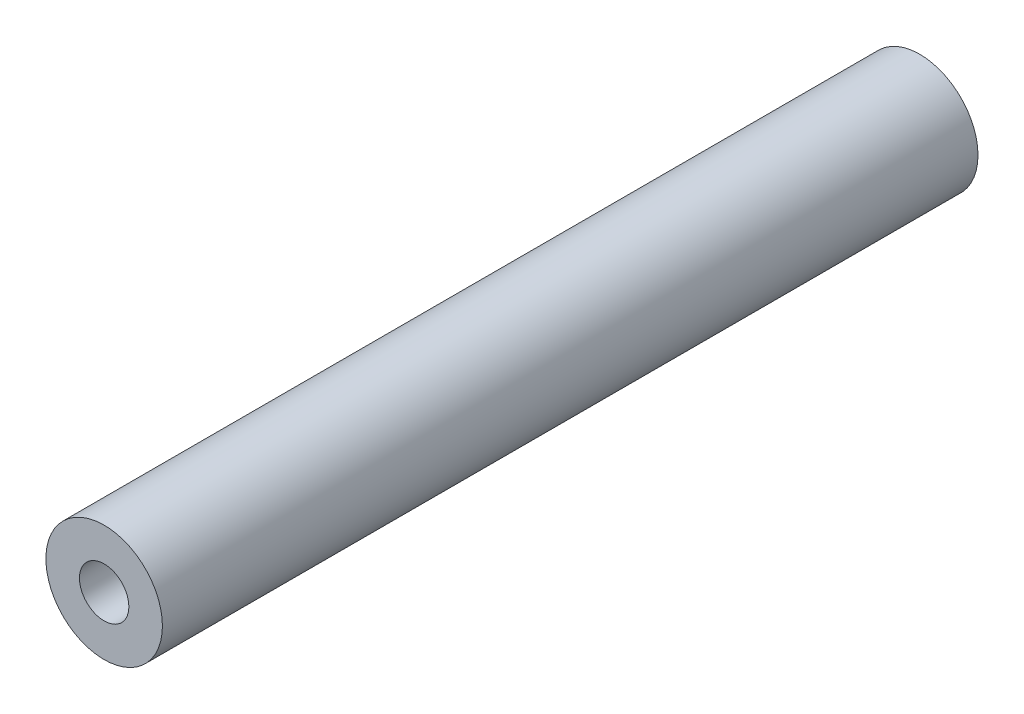
SolidWorks part; units mm, degrees
material "6061-T6 (SS)"
ref_plane "Front Plane" through (0, 0, 0) normal (0, 0, 1) x (1, 0, 0)
ref_plane "Top Plane" through (0, 0, 0) normal (0, 1, 0) x (1, 0, 0)
ref_plane "Right Plane" through (0, 0, 0) normal (1, 0, 0) x (0, 0, -1)
sketch "Sketch1" plane through (0, 0, 0) normal (0, 0, 1) x (1, 0, 0)
  circle A0 centre (0, 0) radius 4.7625
  dimension "D1" = 9.525
extrude "Boss-Extrude1" add sketch "Sketch1" along normal mid plane 66.675
hole_wizard "#10-32 Tapped Hole1" positions "3DSketch1" profile "Sketch2" tap size "#10-32" standard "ANSI Inch"
sketch3d "3DSketch1"
  line L0 (0, 0, 33.3375) -> (0, 0, -33.3375) construction
  point P0 (0, 0, 33.3375)
  point P4 (0, 0, -33.3375)
sketch "Sketch2" plane through (0, 0, 33.3375) normal (1, 0, 0) x (0, -1, 0)
  line L0 (0, 0) -> (0, 13.1513)
  line L1 (0, 13.1513) -> (2.0193, 11.938)
  line L2 (2.0193, 11.938) -> (2.0193, 0)
  line L5 (2.0193, 0) -> (0, 0)
  line L10 (0, 13.1513) -> (-2.0193, 11.938) construction
  line L11 (0, -6.35) -> (0, 107.95) construction
  dimension "Tap Drill Dia." = 4.0386
  dimension "Tap Drill Depth" = 11.938
  dimension "Drill Angle" = 118
cosmetic thread "Hole Thread1"
cosmetic thread "Hole Thread2"
